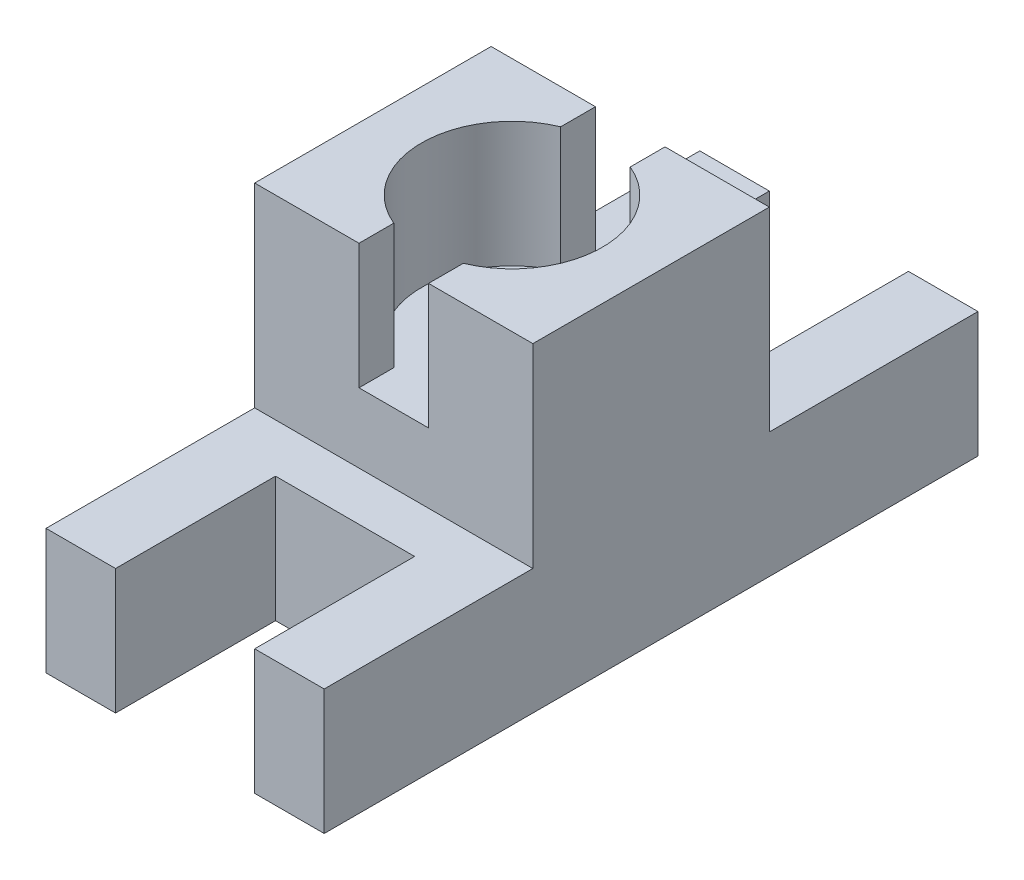
SolidWorks part; units mm, degrees
ref_plane "Alzado" through (0, 0, 0) normal (0, 0, 1) x (1, 0, 0)
ref_plane "Planta" through (0, 0, 0) normal (0, 1, 0) x (1, 0, 0)
ref_plane "Vista lateral" through (0, 0, 0) normal (1, 0, 0) x (0, 0, -1)
sketch "Croquis2" plane through (0, 0, 0) normal (1, 0, 0) x (0, 0, -1)
  line L0 (17, 9) -> (47, 9)
  line L1 (-47, 9) -> (-17, 9)
  line L2 (-47, 9) -> (-47, -9)
  line L3 (-47, -9) -> (47, -9)
  line L4 (47, 9) -> (47, -9)
  line L5 (-17, 37) -> (17, 37)
  line L6 (-17, 37) -> (-17, 9)
  line L8 (17, 37) -> (17, 9)
  point P8 (0, 37)
  point P10 (47, 0)
  dimension "D1" = 94
  dimension "D2" = 46
  dimension "D3" = 18
  dimension "D4" = 34
extrude "Saliente-Extruir1" add sketch "Croquis2" against normal blind 40
sketch "Croquis3" plane through (0, 9, 0) normal (0, 1, 0) x (1, 0, 0)
  line L0 (-57.7309, 0) -> (57.7309, 0) construction
  line L1 (-40, 47) -> (0, 47) construction
  line L2 (-10, 47) -> (-30, 47)
  line L3 (-10, 47) -> (-10, 24)
  line L4 (-10, 24) -> (-30, 24)
  line L5 (-30, 47) -> (-30, 24)
  line L6 (-10, -24) -> (-30, -24)
  line L7 (-30, -47) -> (-30, -24)
  line L8 (-10, -47) -> (-30, -47)
  line L9 (-10, -47) -> (-10, -24)
  point P3 (0, 0)
  point P10 (-20, 47)
  point P11 (-20, 47)
  dimension "D1" = 20
  dimension "D2" = 23
extrude "Cortar-Extruir1" cut sketch "Croquis3" against normal through all
sketch "Croquis4" plane through (0, 37, 0) normal (0, 1, 0) x (1, 0, 0)
  line L0 (-40, 17) -> (0, 17) construction
  line L1 (-25, 17) -> (-15, 17)
  line L2 (-25, 17) -> (-25, 12)
  line L3 (-25, -17) -> (-15, -17)
  line L4 (-15, 17) -> (-15, 12)
  line L5 (-40, -17) -> (0, -17) construction
  line L6 (-15, -12) -> (-15, -17)
  line L7 (-25, -12) -> (-25, -17)
  arc A0 (-25, 12) -> (-25, -12) centre (-20, 0) ccw
  arc A1 (-15, -12) -> (-15, 12) centre (-20, 0) ccw
  point P6 (-20, 17)
  point P7 (-20, 17)
  point P10 (-20, -17)
  point P13 (0, 0)
  point P15 (0, 0)
  point P19 (-20, 0)
  dimension "D2" = 26
  dimension "D1" = 10
extrude "Cortar-Extruir2" cut sketch "Croquis4" against normal blind 18
